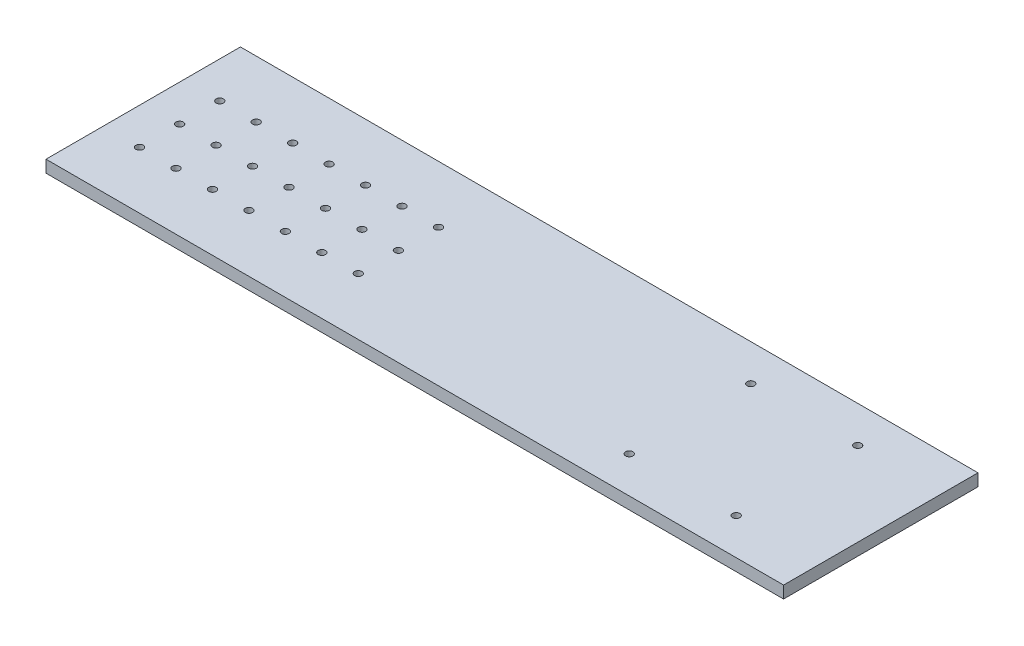
SolidWorks part; units mm, degrees
ref_plane "Front Plane" through (0, 0, 0) normal (0, 0, 1) x (1, 0, 0)
ref_plane "Top Plane" through (0, 0, 0) normal (0, 1, 0) x (1, 0, 0)
ref_plane "Right Plane" through (0, 0, 0) normal (1, 0, 0) x (0, 0, -1)
sketch "Sketch1" plane through (0, 0, 0) normal (0, 1, 0) x (1, 0, 0)
  line L1 (-303.5, 80) -> (303.5, 80)
  line L2 (-303.5, 80) -> (-303.5, -80)
  line L3 (-303.5, -80) -> (303.5, -80)
  line L4 (303.5, 80) -> (303.5, -80)
  line L5 (-303.5, 80) -> (303.5, -80) construction
  line L6 (-303.5, -80) -> (303.5, 80) construction
  point P0 (0, 0)
  dimension "D1" = 607
  dimension "D2" = 160
extrude "Boss-Extrude1" add sketch "Sketch1" along normal blind 10
sketch "Sketch2" plane through (0, 0, 0) normal (0, -1, 0) x (1, 0, 0)
  line L0 (-303.5, 0) -> (303.5, 0) construction
  line L1 (-303.5, -80) -> (-303.5, 80) construction
  line L2 (303.5, 80) -> (303.5, -80) construction
  line L3 (-153.5, 33) -> (-153.5, -61.863) construction
  line L4 (190.5, 80) -> (190.5, -80) construction
  line L5 (-303.5, 80) -> (303.5, 80) construction
  line L6 (303.5, -80) -> (-303.5, -80) construction
  circle A0 centre (-93.5, -33) radius 3
  circle A1 centre (-123.5, -33) radius 3
  circle A2 centre (-153.5, -33) radius 3
  circle A3 centre (-183.5, -33) radius 3
  circle A4 centre (-183.5, 0) radius 3
  circle A5 centre (-183.5, 33) radius 3
  circle A6 centre (-213.5, 33) radius 3
  circle A7 centre (-153.5, 0) radius 3
  circle A8 centre (-213.5, -33) radius 3
  circle A9 centre (-153.5, 33) radius 3
  circle A10 centre (-123.5, 0) radius 3
  circle A11 centre (-123.5, 33) radius 3
  circle A12 centre (-93.5, 0) radius 3
  circle A13 centre (-93.5, 33) radius 3
  circle A14 centre (234.5, 50) radius 3
  circle A15 centre (146.5, 50) radius 3
  circle A16 centre (146.5, -50) radius 3
  circle A17 centre (234.5, -50) radius 3
  circle A18 centre (-243.5, 33) radius 3
  circle A19 centre (-243.5, 0) radius 3
  circle A20 centre (-213.5, 0) radius 3
  circle A21 centre (-243.5, -33) radius 3
  circle A22 centre (-273.5, 33) radius 3
  circle A23 centre (-273.5, 0) radius 3
  circle A24 centre (-273.5, -33) radius 3
  dimension "D1" = 90
  dimension "D5" = 88
  dimension "D8" = 3
  dimension "D6" = 50
  dimension "D7" = 44
  dimension "D2" = 5
  dimension "D3" = 300
  dimension "D4" = 33
extrude "Cut-Extrude1" cut sketch "Sketch2" against normal up to surface (10 mm away) up to face at (0, 10, 0)
